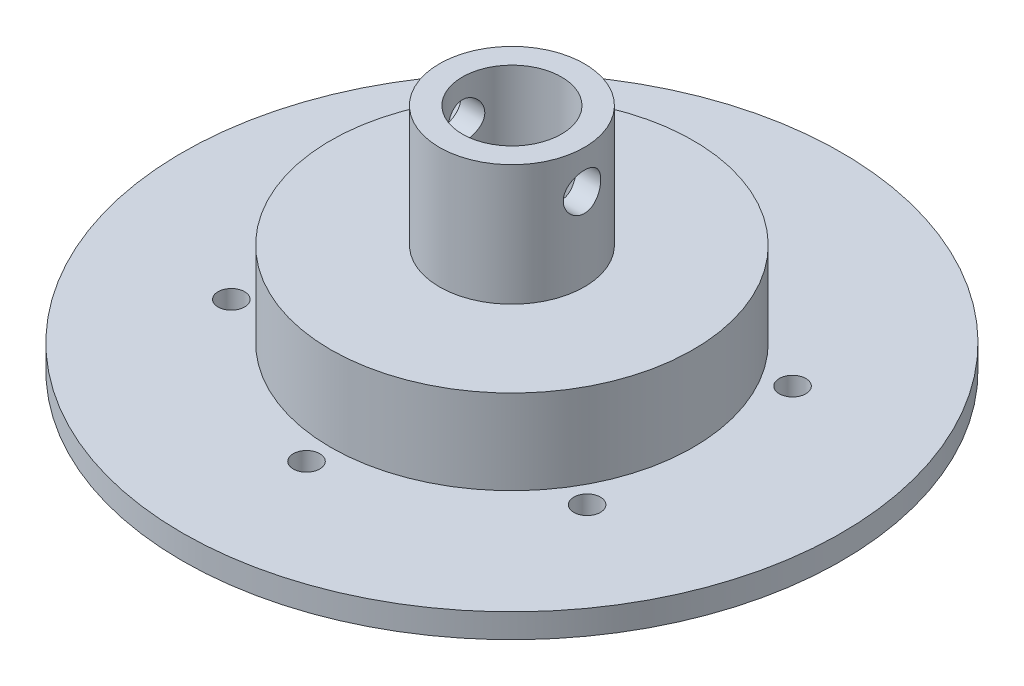
SolidWorks part; units mm, degrees
ref_plane "Front Plane" through (0, 0, 0) normal (0, 0, 1) x (1, 0, 0)
ref_plane "Top Plane" through (0, 0, 0) normal (0, 1, 0) x (1, 0, 0)
ref_plane "Right Plane" through (0, 0, 0) normal (1, 0, 0) x (0, 0, -1)
sketch "Sketch1" plane through (0, 0, 0) normal (0, 1, 0) x (1, 0, 0)
  line L0 (0, 0) -> (0, 17) construction
  circle A0 centre (0, 0) radius 27.2742
  circle A1 centre (0, 17) radius 1
  circle A2 centre (14.7224, 8.5) radius 1
  circle A3 centre (14.7224, -8.5) radius 1
  circle A4 centre (0, -17) radius 1
  circle A5 centre (-14.7224, -8.5) radius 1
  circle A6 centre (-14.7224, 8.5) radius 1
  circle A7 centre (0, 0) radius 12.5
  point P17 (0, 0)
  dimension "D1" = 17
  dimension "D2" = 2
  dimension "D4" = 25
  dimension "D3" = 6
extrude "Boss-Extrude1" add sketch "Sketch1" along normal blind 2
sketch "Sketch4" plane through (0, 2, 0) normal (0, 1, 0) x (1, 0, 0)
  circle A0 centre (0, 0) radius 15
  dimension "D1" = 30
extrude "Boss-Extrude3" add sketch "Sketch4" along normal blind 7
sketch "Sketch5" plane through (0, 9, 0) normal (0, 1, 0) x (1, 0, 0)
  circle A0 centre (0, 0) radius 6
  circle A1 centre (0, 0) radius 4.1
  dimension "D1" = 12
  dimension "D2" = 8.2
extrude "Boss-Extrude4" add sketch "Sketch5" along normal blind 10
sketch "Sketch6" plane through (0, 0, 0) normal (1, 0, 0) x (0, 0, -1)
  circle A0 centre (0, 15.8186) radius 1.55
  dimension "D1" = 3.1
extrude "Cut-Extrude1" cut sketch "Sketch6" against normal through all both and the other way through all
sketch "Sketch7" plane through (0, 2, 0) normal (0, -1, 0) x (1, 0, 0)
  circle A0 centre (0, 0) radius 7.5
  dimension "D1" = 15
extrude "Cut-Extrude2" cut sketch "Sketch7" against normal blind 5
sketch "Sketch9" plane through (0, 2, 0) normal (0, 1, 0) x (1, 0, 0)
  line L0 (0, 0) -> (0, 17) construction
  circle A0 centre (0, 17) radius 1.1
  circle A1 centre (14.7224, 8.5) radius 1.1
  circle A2 centre (14.7224, -8.5) radius 1.1
  circle A3 centre (0, -17) radius 1.1
  circle A4 centre (-14.7224, -8.5) radius 1.1
  circle A5 centre (-14.7224, 8.5) radius 1.1
  point P16 (0, 0)
  dimension "D1" = 6
  dimension "D2" = 2.2
extrude "Cut-Extrude3" cut sketch "Sketch9" along normal through all both and the other way through all
